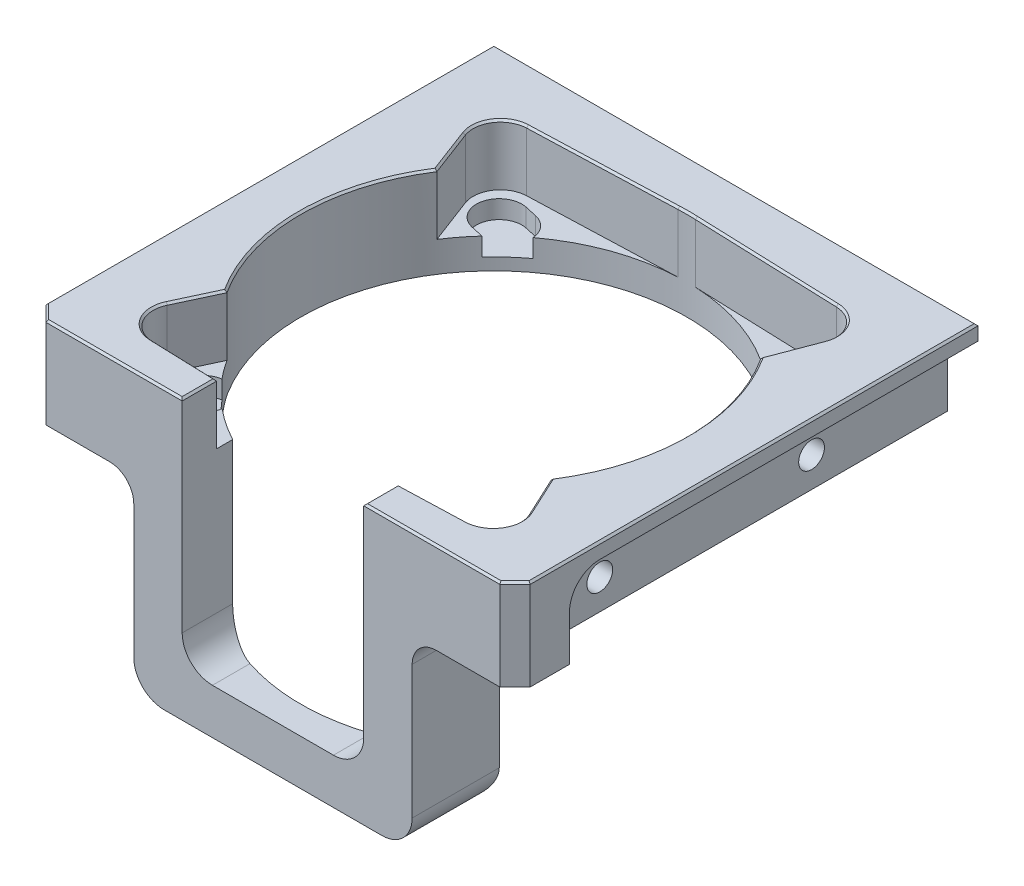
SolidWorks part; units mm, degrees
material "6061-T6 (SS)"
ref_plane "Front Plane" through (0, 0, 0) normal (0, 0, 1) x (1, 0, 0)
ref_plane "Top Plane" through (0, 0, 0) normal (0, 1, 0) x (1, 0, 0)
ref_plane "Right Plane" through (0, 0, 0) normal (1, 0, 0) x (0, 0, -1)
sketch "Sketch1" plane through (0, 0, 0) normal (0, 1, 0) x (1, 0, 0)
  line L1 (50.8, 48.5775) -> (-50.8, 48.5775)
  line L2 (50.8, 48.5775) -> (50.8, -48.5775)
  line L3 (50.8, -48.5775) -> (-50.8, -48.5775)
  line L4 (-50.8, 48.5775) -> (-50.8, -48.5775)
  line L5 (50.8, 48.5775) -> (-50.8, -48.5775) construction
  line L6 (50.8, -48.5775) -> (-50.8, 48.5775) construction
  point P0 (0, 0)
  dimension "D1" = 97.155
  dimension "D2" = 101.6
extrude "Boss-Extrude1" add sketch "Sketch1" along normal blind 58.42
sketch "Sketch2" plane through (0, 0, 48.5775) normal (0, 0, 1) x (1, 0, 0)
  line L0 (-50.8, 58.42) -> (-50.8, 0) construction
  line L1 (-50.8, 39.37) -> (-29.21, 39.37)
  line L2 (-50.8, 39.37) -> (-50.8, 0)
  line L3 (-50.8, 0) -> (-29.21, 0)
  line L4 (-29.21, 39.37) -> (-29.21, 0)
  line L5 (-50.8, 0) -> (50.8, 0) construction
  line L6 (50.8, 58.42) -> (50.8, 0) construction
  line L7 (50.8, 39.37) -> (29.21, 39.37)
  line L8 (50.8, 39.37) -> (50.8, 0)
  line L9 (50.8, 0) -> (29.21, 0)
  line L10 (29.21, 39.37) -> (29.21, 0)
  line L11 (-50.8, 58.42) -> (50.8, 58.42) construction
  dimension "D1" = 19.05
  dimension "D2" = 21.59
extrude "Cut-Extrude1" cut sketch "Sketch2" against normal through all
sketch "Sketch3" plane through (0, 58.42, 0) normal (0, 1, 0) x (1, 0, 0)
  line L0 (50.8, 48.5775) -> (-50.8, 48.5775) construction
  circle A0 centre (0, -2.2225) radius 40.513
  dimension "D2" = 81.026
  dimension "D1" = 50.8
extrude "Cut-Extrude2" cut sketch "Sketch3" against normal through all
sketch "Sketch4" plane through (0, 0, 0) normal (0, -1, 0) x (1, 0, 0)
  line L3 (-29.21, -25.8502) -> (-29.21, -48.5775)
  line L4 (-29.21, -48.5775) -> (29.21, -48.5775)
  line L5 (29.21, -48.5775) -> (29.21, -25.8502)
  line L6 (-29.21, -25.8502) -> (-29.21, -48.5775)
  line L7 (-29.21, -48.5775) -> (29.21, -48.5775)
  line L8 (29.21, -48.5775) -> (29.21, -25.8502)
  arc A1 (-29.21, -25.8502) -> (29.21, -25.8502) centre (0, 2.2225) ccw
  arc A2 (-29.21, -25.8502) -> (29.21, -25.8502) centre (0, 2.2225) ccw
  dimension "D1" = 0
extrude "Cut-Extrude3" cut sketch "Sketch4" against normal up to surface (39.37 mm away) up to face at (-38.2905, 39.37, 0.7408)
sketch "Sketch5" plane through (0, 0, 48.5775) normal (0, 0, 1) x (1, 0, 0)
  line L0 (-50.8, 58.42) -> (50.8, 58.42) construction
  line L1 (-19.05, 58.42) -> (19.05, 58.42)
  line L2 (-19.05, 58.42) -> (-19.05, 9.525)
  line L3 (-19.05, 9.525) -> (19.05, 9.525)
  line L4 (19.05, 58.42) -> (19.05, 9.525)
  point P6 (0, 9.525)
  dimension "D1" = 38.1
  dimension "D2" = 48.895
extrude "Cut-Extrude4" cut sketch "Sketch5" against normal up to next
fillet "Fillet1" radius 6.35 4 edges at (-29.21, 0, 39.4364) (29.21, 0, 39.4364) (-19.05, 9.525, 43.2774) (19.05, 9.525, 43.2774)
fillet "Fillet2" radius 5.08 2 edges at (-29.21, 39.37, 39.4364) (29.21, 39.37, 39.4364)
chamfer "Chamfer1" distance 3.175 angle 45 2 edges at (50.8, 48.895, 48.5775) (-50.8, 48.895, 48.5775)
sketch "Sketch6" plane through (-50.8, 0, 0) normal (-1, 0, 0) x (0, 0, 1)
  line L0 (-48.5775, 58.42) -> (-48.5775, 39.37) construction
  line L1 (-48.5775, 55.245) -> (30.7975, 55.245)
  line L2 (-48.5775, 55.245) -> (-48.5775, 39.37)
  line L3 (-48.5775, 39.37) -> (37.1475, 39.37)
  line L4 (37.1475, 48.895) -> (37.1475, 39.37)
  line L5 (23.7979, 39.37) -> (48.5775, 39.37) construction
  line L6 (-48.5775, 58.42) -> (45.4025, 58.42) construction
  arc A0 (37.1475, 48.895) -> (30.7975, 55.245) centre (30.7975, 48.895) ccw
  point P12 (37.1475, 55.245)
  dimension "D3" = 6.35
  dimension "D1" = 85.725
  dimension "D2" = 3.175
extrude "Cut-Extrude5" cut sketch "Sketch6" against normal blind 6.35
sketch "Sketch7" plane through (-44.45, 0, 0) normal (-1, 0, 0) x (0, 0, 1)
  line L0 (-48.5775, 55.245) -> (-48.5775, 39.37) construction
  line L1 (30.7975, 55.245) -> (-48.5775, 55.245) construction
  point P0 (24.4475, 45.72)
  point P1 (-20.0025, 45.72)
  dimension "D1" = 44.45
  dimension "D2" = 28.575
  dimension "D3" = 9.525
hole_wizard "Tap Drill for 1/4-28 Tap1" positions "3DSketch1" profile "Sketch8" hole size "1/4-28" standard "ANSI Inch"
sketch3d "3DSketch1"
  point P0 (-44.45, 45.72, -20.0025)
  point P3 (-44.45, 45.72, 24.4475)
sketch "Sketch8" plane through (-44.45, 45.72, -20.0025) normal (0, 1, 0) x (0, 0, 1)
  line L0 (0, 0) -> (0, 8.7374)
  line L1 (0, 8.7374) -> (2.7051, 7.112)
  line L2 (2.7051, 7.112) -> (2.7051, 0)
  line L5 (2.7051, 0) -> (0, 0)
  line L10 (0, 8.7374) -> (-2.7051, 7.112) construction
  line L11 (0, -6.35) -> (0, 107.95) construction
  dimension "Hole Dia." = 5.4102
  dimension "Hole Depth" = 7.112
  dimension "Drill Angle" = 118
hole_wizard "Tap Drill for 1/4-28 Tap2" positions "3DSketch2" profile "Sketch10" hole size "1/4-28" standard "ANSI Inch"
sketch3d "3DSketch2"
  line L1 (50.8, 58.42, -48.5775) -> (-50.8, 58.42, -48.5775) construction
  line L2 (50.8, 58.42, -48.5775) -> (50.8, 39.37, -48.5775) construction
  point P0 (38.1, 48.895, -48.5775)
  point P2 (-38.1, 48.895, -48.5775)
  dimension "D1" = 9.525
  dimension "D2" = 76.2
  dimension "D3" = 12.7
sketch "Sketch10" plane through (38.1, 48.895, -48.5775) normal (1, 0, 0) x (0, 1, 0)
  line L0 (0, 0) -> (0, 11.43)
  line L1 (0, 11.43) -> (2.7051, 9.8046)
  line L2 (2.7051, 9.8046) -> (2.7051, 0)
  line L5 (2.7051, 0) -> (0, 0)
  line L10 (0, 11.43) -> (-2.7051, 9.8046) construction
  line L11 (0, -6.35) -> (0, 107.95) construction
  dimension "Hole Dia." = 5.4102
  dimension "Hole Depth" = 11.43
  dimension "Drill Angle" = 118
sketch "Sketch12" plane through (0, 58.42, 0) normal (0, 1, 0) x (1, 0, 0)
  line L0 (-32.8435, -35.1739) -> (32.8435, -35.1739) construction
  line L1 (-32.2961, 31.4452) -> (32.2961, 31.4452) construction
  line L2 (0, 31.4452) -> (0, -35.1739) construction
  line L3 (-1.8431, 38.2486) -> (-32.4995, 37.1566)
  line L4 (1.8431, 38.2486) -> (32.4995, 37.1566)
  line L6 (-33.9928, 19.8181) -> (-37.6386, 29.4158)
  line L7 (-34.0327, -24.2015) -> (-38.023, -32.7587)
  line L8 (-33.033, -40.8858) -> (-9.2034, -41.6763)
  line L9 (9.2034, -41.6763) -> (33.033, -40.8858)
  line L10 (38.023, -32.7587) -> (34.0327, -24.2015)
  line L11 (33.9928, 19.8181) -> (37.6386, 29.4158)
  line L12 (50.8, -45.4025) -> (50.8, 48.5775) construction
  line L13 (-50.8, 48.5775) -> (-50.8, -45.4025) construction
  line L15 (-47.625, -48.5775) -> (-19.05, -48.5775) construction
  line L16 (50.8, 48.5775) -> (-50.8, 48.5775) construction
  circle A0 centre (32.2961, 31.4452) radius 5.715
  circle A1 centre (-32.2961, 31.4452) radius 5.715
  circle A2 centre (-32.8435, -35.1739) radius 5.715
  circle A3 centre (32.8435, -35.1739) radius 5.715
  arc A4 (19.05, -37.9772) -> (-19.05, -37.9772) centre (0, -2.2225) ccw construction
  arc A5 (19.05, -37.9772) -> (-19.05, -37.9772) centre (0, -2.2225) ccw
  line M19 (-19.05, -48.5775) -> (-19.05, -37.9772)
  arc M20 (-19.05, -37.9772) -> (19.05, -37.9772) centre (0, -2.2225) cw
  line M21 (19.05, -37.9772) -> (19.05, -48.5775)
  dimension "D5" = 11.43
  dimension "D1" = 64.5922
  dimension "D2" = 65.6869
  dimension "D3" = 32.9514
  dimension "D4" = 33.6677
  dimension "D6" = 2.04
  dimension "D8" = 20.8
  dimension "D9" = 25
  dimension "D10" = 25
  dimension "D11" = 20.8
  dimension "D12" = 1.9
extrude "Cut-Extrude6" cut sketch "Sketch12" against normal blind 12.7 contours A1 | A1 L6 L3 M20 | A0 L4 L11 M20 | A0 | A3 | A3 L10 L9 M20 M21 | A2 L8 L7 M19 M20 | A2
sketch "Sketch13" plane through (0, 45.72, 0) normal (0, 1, 0) x (1, 0, 0)
  line L0 (-31.496, 30.3886) -> (-28.956, 29.8272) construction
  line L1 (-30.4683, 35.0389) -> (-27.9283, 34.4775)
  line L2 (-32.5237, 25.7383) -> (-29.9837, 25.1769)
  line L3 (-30.48, -32.827) -> (-32.2123, -34.1274) construction
  line L4 (-27.6207, -36.6356) -> (-29.353, -37.9361)
  line L5 (-33.3393, -29.0183) -> (-35.0716, -30.3188)
  arc A0 (-30.4683, 35.0389) -> (-32.5237, 25.7383) centre (-31.496, 30.3886) ccw
  arc A1 (-29.9837, 25.1769) -> (-27.9283, 34.4775) centre (-28.956, 29.8272) ccw
  arc A2 (-27.6207, -36.6356) -> (-33.3393, -29.0183) centre (-30.48, -32.827) ccw
  arc A3 (-35.0716, -30.3188) -> (-29.353, -37.9361) centre (-32.2123, -34.1274) ccw
  circle A5 centre (0, -2.2225) radius 40.513
  arc A6 (34.0327, -24.2015) -> (33.9928, 19.8181) centre (0, -2.2225) ccw construction
  point P2 (-30.226, 30.1079)
  point P7 (-31.3461, -33.4772)
  arc M5 (-33.9928, 19.8181) -> (-1.8431, 38.2486) centre (0, -2.2225) cw
  dimension "D9" = 4.7625
  dimension "D10" = 4.7625
  dimension "D1" = 30.48
  dimension "D2" = 32.2123
  dimension "D3" = 28.956
  dimension "D4" = 31.496
  dimension "D5" = 29.8272
  dimension "D6" = 30.3886
  dimension "D7" = 32.827
  dimension "D8" = 34.1274
extrude "Cut-Extrude7" cut sketch "Sketch13" against normal blind 3.81 contours A1 L1 A0 L2 M5 | A5 A2 L5 A3 L4
mirror "Mirror1" about plane through (0, 0, 0) normal (1, 0, 0) of "Cut-Extrude7", "Tap Drill for 1/4-28 Tap1", "Cut-Extrude5"
chamfer "Chamfer2" distance 0.4 angle 45 24 edges at (-33.3375, 58.42, 48.5775) (-49.2125, 58.42, 46.99) (-50.8, 58.42, -1.5875) (0, 58.42, -48.5775) (50.8, 58.42, -1.5875) (49.2125, 58.42, 46.99) (33.3375, 58.42, 48.5775) (19.05, 58.42, 44.9636) (26.0415, 58.42, 41.1177) (37.7137, 58.42, 38.1643) (36.0279, 58.42, 28.4801) (40.513, 58.42, 2.1858) (35.8157, 58.42, -24.617) (37.0573, 58.42, -34.6062) (17.1713, 58.42, -37.7026) (0, 58.42, -38.2905) (-17.1713, 58.42, -37.7026) (-37.0573, 58.42, -34.6062) (-35.8157, 58.42, -24.617) (-40.513, 58.42, 2.1858) (-36.0279, 58.42, 28.4801) (-37.7137, 58.42, 38.1643) (-26.0415, 58.42, 41.1177) (-19.05, 58.42, 44.9636)
